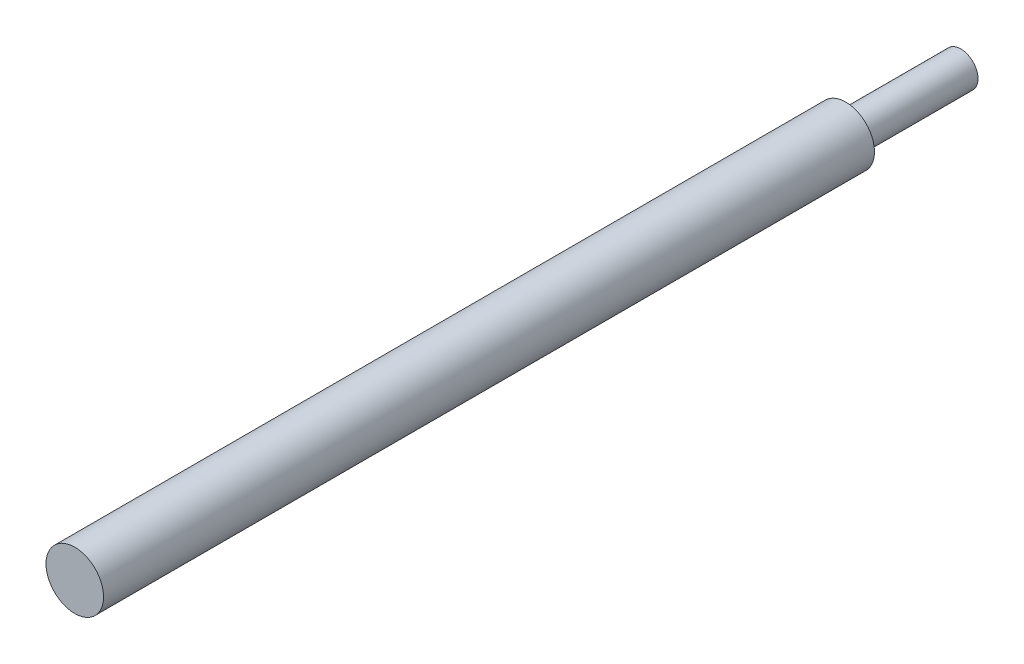
SolidWorks part; units mm, degrees
material "Cuivre"
ref_plane "Plan de face" through (0, 0, 0) normal (0, 0, 1) x (1, 0, 0)
ref_plane "Plan de dessus" through (0, 0, 0) normal (0, 1, 0) x (1, 0, 0)
ref_plane "Plan de droite" through (0, 0, 0) normal (1, 0, 0) x (0, 0, -1)
sketch "Esquisse1" plane through (0, 0, 0) normal (0, 0, 1) x (1, 0, 0)
  circle A0 centre (0, 0) radius 2.5
  dimension "D1" = 5
extrude "Boss.-Extru.1" add sketch "Esquisse1" along normal blind 77
sketch "Esquisse3" plane through (0, 0, 0) normal (0, 0, -1) x (-1, 0, 0)
  circle A0 centre (0, 0) radius 2.5
  circle A1 centre (0, 0) radius 1.5
  circle A2 centre (0, 0) radius 2.5 construction
  dimension "D1" = 1
extrude "Enlèv. mat.-Extru.2" cut sketch "Esquisse3" against normal blind 10
